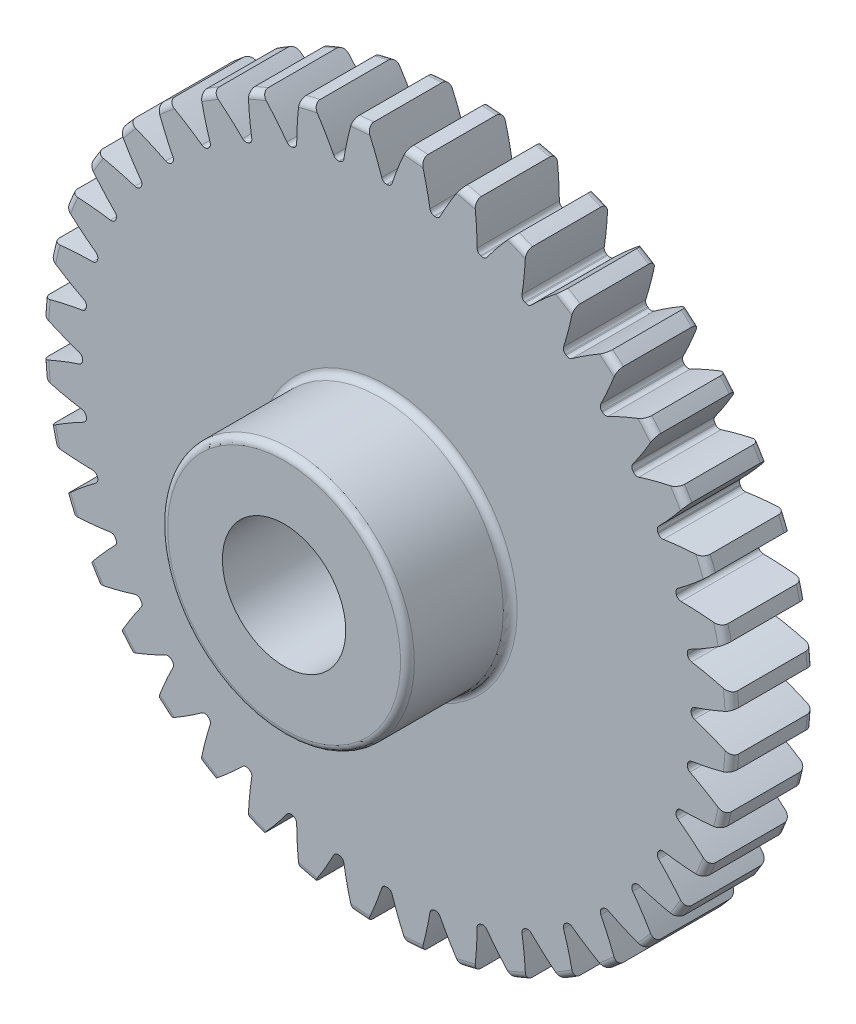
SolidWorks part; units mm, degrees
ref_plane "Front Plane" through (0, 0, 0) normal (0, 0, 1) x (1, 0, 0)
ref_plane "Top Plane" through (0, 0, 0) normal (0, 1, 0) x (1, 0, 0)
ref_plane "Right Plane" through (0, 0, 0) normal (1, 0, 0) x (0, 0, -1)
sketch "Sketch1" plane through (0, 0, 0) normal (0, 0, 1) x (1, 0, 0)
  line L0 (-508, 0) -> (508, 0) construction
  circle A0 centre (0, 0) radius 16.8 construction
  circle A1 centre (0, 0) radius 16 construction
  circle A2 centre (0, 0) radius 14.8 construction
  circle A3 centre (0, 0) radius 6 construction
  circle A4 centre (0, 0) radius 3 construction
  dimension "D1" = 2
  dimension "OD" = 33.6
  dimension "Pitch Dia." = 32
  dimension "D2" = 0.8
  dimension "D3" = 2
  dimension "Root Dia." = 29.6
  dimension "Hub Dia." = 12
  dimension "Shaft Dia." = 6
  dimension "Number of Teeth" = 1016
sketch "Sketch2" plane through (0, 0, 0) normal (1, 0, 0) x (0, 0, -1)
  line L0 (0, 0) -> (-4, 0) construction
  line L1 (-4, 0) -> (-9, 0) construction
  dimension "Overall Width" = 9
  dimension "Face Width" = 4
sketch "Sketch4" plane through (0, 0, 0) normal (1, 0, 0) x (0, 0, -1)
  line L0 (-9, 3) -> (-9, 6)
  line L1 (-9, 6) -> (-4, 6)
  line L2 (-4, 6) -> (-4, 16.8)
  line L3 (-4, 16.8) -> (0, 16.8)
  line L4 (0, 16.8) -> (0, 3)
  line L5 (-4, 6) -> (-4, 0) construction
  line L6 (0, 16.8) -> (0, -16.8) construction
  line L7 (-4, 6) -> (0, 6) construction
  line L12 (-9, 3) -> (0, 3)
revolve "Revolve1" add sketch "Sketch4" angle 360 about L1
fillet "Fillet2" radius 0.336 4 edges at (0, 6, 9) (0, 6, 4) (0, 16.8, 4) (0, 16.8, 0)
sketch "Sketch7" plane through (0, 0, 4) normal (0, 0, 1) x (1, 0, 0)
  line L0 (0, 0) -> (0, 16.8) construction
  line L1 (0.6282, 15.9877) -> (0.9495, 16.7731) construction
  line L3 (1.3181, 16.7482) -> (1.2553, 15.9507) construction
  line L4 (1.2553, 15.9507) -> (1.1612, 14.7544) construction
  line L5 (0, 0) -> (1.1612, 14.7544) construction
  line L6 (0.6282, 15.9877) -> (0, 0) construction
  line L7 (0.6282, 15.9877) -> (0.6596, 16.787) construction
  line L8 (0.6282, 15.9877) -> (0, 0) construction
  circle A0 centre (0, 0) radius 16.8 construction
  arc A1 (-0.0216, 14.8) -> (0.0216, 14.8) centre (0, 0) cw
  circle A2 centre (0, 0) radius 14.8 construction
  arc A3 (-0.6282, 15.9877) -> (0.6282, 15.9877) centre (0, 0) cw construction
  circle A4 centre (0, 0) radius 16 construction
  arc A5 (1.6619, 16.7176) -> (0.9737, 16.7718) centre (0, 0) ccw construction
  arc A6 (0.6282, 15.9877) -> (1.8806, 15.8891) centre (0, 0) cw construction
  arc A7 (-0.9737, 16.7718) -> (0.9737, 16.7718) centre (0, 0) cw
  arc A8 (0.2497, 14.9645) -> (0.9737, 16.7718) centre (15.4368, 9.9293) cw
  arc A9 (-0.2497, 14.9645) -> (-0.9737, 16.7718) centre (-15.4368, 9.9293) ccw
  arc A10 (-0.0216, 14.8) -> (-0.2497, 14.9645) centre (-0.0219, 15.04) cw
  arc A11 (0.0216, 14.8) -> (0.2497, 14.9645) centre (0.0219, 15.04) ccw
  point P26 (-0.1958, 14.7987)
  point P29 (0.1958, 14.7987)
  dimension "D4" = 0.24
  dimension "D5" = 16
  dimension "D2" = 1.2566
  dimension "D1" = 2.5133
  dimension "D3" = 20
extrude "Cut-Extrude2" cut sketch "Sketch7" against normal through all
pattern_circular "CirPattern1" count 40 over 360 about axis through (0, 0, 0) along (0, 0, 1) of "Cut-Extrude2"
equation "\"D1@Sketch1\"=2.5*(\"Pitch Dia.@Sketch1\"/\"Number of Teeth@Sketch1\")"
equation "\"D1@CirPattern1\"=\"Number of Teeth@Sketch1\""
equation "\"D1@Fillet2\"=\"OD@Sketch1\"*.01"
equation "\"D1@Sketch7\"=3.14159*(\"Pitch Dia.@Sketch1\"/\"Number of Teeth@Sketch1\")"
equation "\"D2@Sketch7\"=\"D1@Sketch7\"/2"
equation "\"D4@Sketch7\"=\"D1@Sketch7\"*.0955"
equation "\"D5@Sketch7\"=\"Pitch Dia.@Sketch1\"/2"
